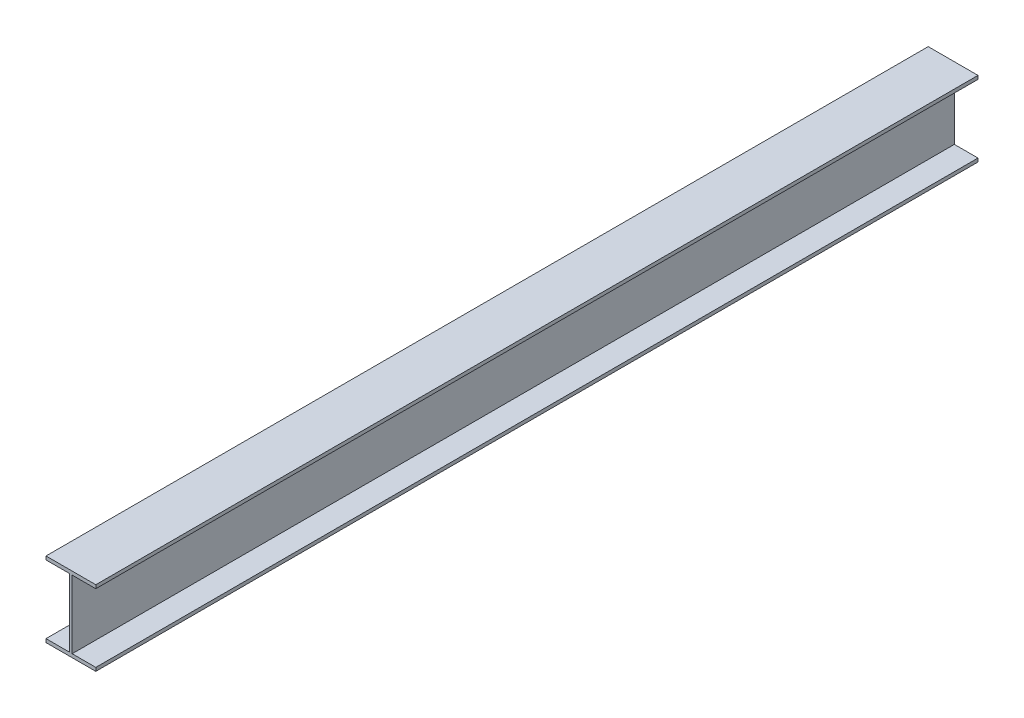
SolidWorks part; units mm, degrees
material "ASTM A992 Steel"
ref_plane "Front" through (0, 0, 0) normal (0, 0, 1) x (1, 0, 0)
ref_plane "Top" through (0, 0, 0) normal (0, 1, 0) x (1, 0, 0)
ref_plane "Right" through (0, 0, 0) normal (1, 0, 0) x (0, 0, -1)
sketch "Sketch1" plane through (0, 0, 0) normal (0, 0, 1) x (1, 0, 0)
  line L0 (0, -0.0002) -> (101.6, -0.0002)
  line L1 (101.6, -0.0002) -> (101.6, -7.1122)
  line L2 (101.6, -7.1122) -> (53.408, -7.1122)
  line L3 (53.408, -7.1122) -> (53.408, -146.0502)
  line L4 (53.408, -146.0502) -> (101.6, -146.0502)
  line L5 (101.6, -146.0502) -> (101.6, -153.1622)
  line L6 (101.6, -153.1622) -> (0, -153.1622)
  line L7 (0, -153.1622) -> (0, -146.0502)
  line L8 (0, -146.0502) -> (47.566, -146.0502)
  line L9 (47.566, -146.0502) -> (47.566, -7.1122)
  line L10 (47.566, -7.1122) -> (0, -7.1122)
  line L11 (0, -7.1122) -> (0, -0.0002)
  line L12 (50.8, -0.0002) -> (50.8, -153.1622) construction
  dimension "D1" = 5.842
  dimension "D2" = 7.112
  dimension "D3" = 7.112
  dimension "D4" = 7.112
  dimension "D5" = 153.162
  dimension "D6" = 50.8
  dimension "D7" = 50.8
  dimension "D8" = 47.566
extrude "Boss-Extrude1" add sketch "Sketch1" along normal blind 1800
sketch "Sketch2" plane through (0, -153.1622, 0) normal (0, -1, 0) x (1, 0, 0)
  line L0 (101.6, 1800) -> (101.6, 0) construction
  line L1 (101.6, 1800) -> (101.6, 0) construction
  line L3 (101.6, 900) -> (101.6, 1050)
  line L4 (101.6, 1050) -> (0, 1050)
  line L5 (0, 900) -> (0, 1050)
  line L6 (0, 1800) -> (0, 0) construction
  line L9 (101.6, 900) -> (101.6, 750)
  line L10 (101.6, 750) -> (0, 750)
  line L11 (0, 900) -> (0, 750)
  point P0 (101.6, 900)
  dimension "D1" = 150
  dimension "D2" = 150
split line "Split Line1"
